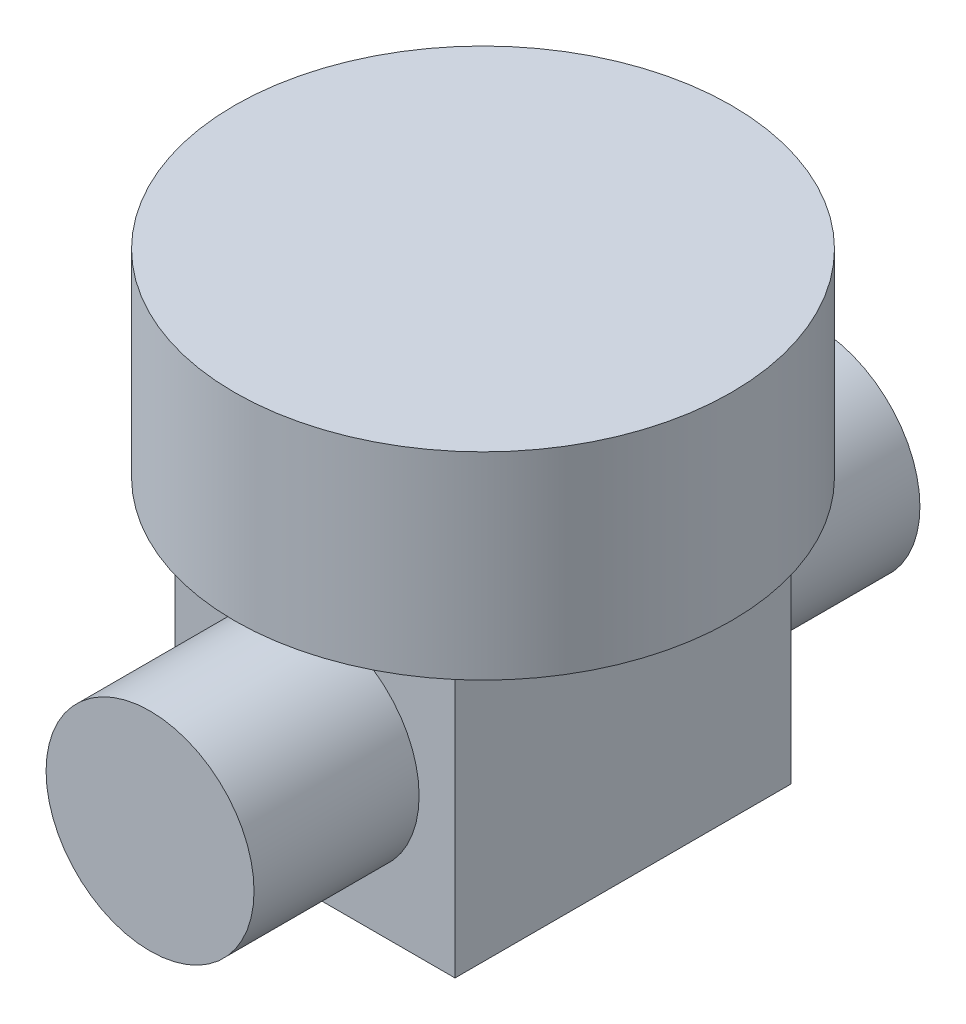
SolidWorks part; units mm, degrees
ref_plane "Front Plane" through (0, 0, 0) normal (0, 0, 1) x (1, 0, 0)
ref_plane "Top Plane" through (0, 0, 0) normal (0, 1, 0) x (1, 0, 0)
ref_plane "Right Plane" through (0, 0, 0) normal (1, 0, 0) x (0, 0, -1)
sketch "Sketch1" plane through (0, 0, 0) normal (0, 1, 0) x (1, 0, 0)
  line L1 (-9.525, -11.43) -> (9.525, -11.43)
  line L2 (-9.525, -11.43) -> (-9.525, 11.43)
  line L3 (-9.525, 11.43) -> (9.525, 11.43)
  line L4 (9.525, -11.43) -> (9.525, 11.43)
  line L5 (-9.525, -11.43) -> (9.525, 11.43) construction
  line L6 (-9.525, 11.43) -> (9.525, -11.43) construction
  point P0 (0, 0)
  dimension "D1" = 19.05
  dimension "D2" = 22.86
extrude "Boss-Extrude1" add sketch "Sketch1" along normal mid plane 19.05
sketch "Sketch2" plane through (0, 9.525, 0) normal (0, 1, 0) x (1, 0, 0)
  circle A0 centre (0, 0) radius 16.9228
  dimension "D1" = 33.8455
extrude "Boss-Extrude2" add sketch "Sketch2" along normal blind 13.462
sketch "Sketch4" plane through (0, 0, 0) normal (0, 0, 1) x (1, 0, 0)
  circle A0 centre (0, 0) radius 7.0803
  dimension "D1" = 14.1605
extrude "Boss-Extrude4" add sketch "Sketch4" along normal mid plane 45.339
